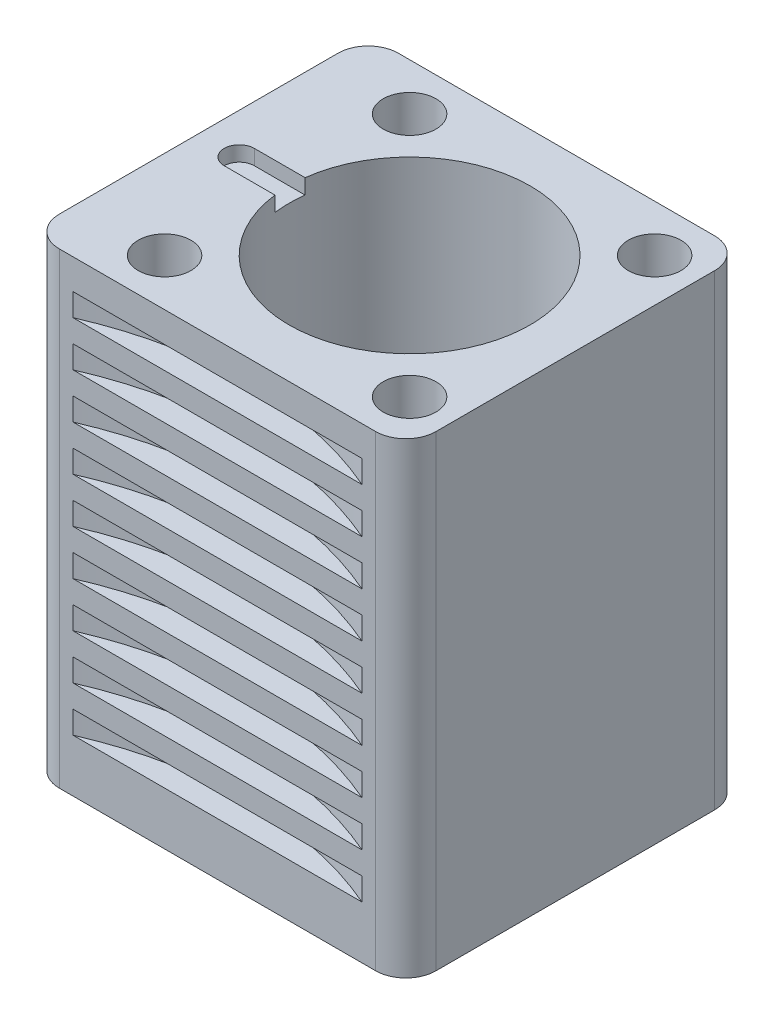
SolidWorks part; units mm, degrees
ref_plane "Front Plane" through (0, 0, 0) normal (0, 0, 1) x (1, 0, 0)
ref_plane "Top Plane" through (0, 0, 0) normal (0, 1, 0) x (1, 0, 0)
ref_plane "Right Plane" through (0, 0, 0) normal (1, 0, 0) x (0, 0, -1)
sketch "Sketch2" plane through (0, 0, 0) normal (0, 1, 0) x (1, 0, 0)
  line L1 (18, 22.5) -> (-24, 22.5)
  line L2 (22, 18.5) -> (22, -18.5)
  line L3 (18, -22.5) -> (-24, -22.5)
  line L4 (-28, 18.5) -> (-28, -18.5)
  arc A0 (-24, 22.5) -> (-28, 18.5) centre (-24, 18.5) ccw
  arc A1 (22, -18.5) -> (18, -22.5) centre (18, -18.5) cw
  arc A2 (-24, -22.5) -> (-28, -18.5) centre (-24, -18.5) cw
  arc A3 (18, 22.5) -> (22, 18.5) centre (18, 18.5) cw
  point P7 (-28, 22.5)
  point P10 (22, -22.5)
  point P15 (22, 22.5)
  dimension "D5" = 4
  dimension "D1" = 50
  dimension "D2" = 45
  dimension "D3" = 22
  dimension "D4" = 22.5
extrude "Boss-Extrude1" add sketch "Sketch2" along normal blind 62
sketch "Sketch3" plane through (0, 0, 0) normal (0, -1, 0) x (1, 0, 0)
  circle A0 centre (0, 0) radius 18
  dimension "D1" = 36
extrude "Boss-Extrude2" add sketch "Sketch3" along normal blind 2
sketch "Sketch4" plane through (0, -2, 0) normal (0, -1, 0) x (1, 0, 0)
  circle A0 centre (0, 0) radius 16
  dimension "D1" = 32
extrude "Cut-Extrude1" cut sketch "Sketch4" against normal through all
sketch "Sketch7" plane through (0, 62, 0) normal (0, 1, 0) x (1, 0, 0)
  line L0 (-28, 18.5) -> (-28, -18.5) construction
  line L1 (-22.61, 2) -> (-11.0093, 2)
  line L3 (-22.61, -2) -> (-11.0093, -2)
  line L4 (-11.0093, 2) -> (-11.0093, -2)
  arc A0 (-22.61, 2) -> (-22.61, -2) centre (-22.61, 0) ccw
  dimension "D1" = 4
  dimension "D2" = 2
  dimension "D3" = 5.39
extrude "Cut-Extrude2" cut sketch "Sketch7" against normal blind 2
sketch "Sketch8" plane through (0, 62, 0) normal (0, 1, 0) x (1, 0, 0)
  line L0 (0, 0) -> (23, 0) construction
  line L1 (0, 0) -> (16.2635, 16.2635) construction
  circle A0 centre (0, 0) radius 23 construction
  circle A1 centre (16.2635, 16.2635) radius 3.5
  circle A2 centre (16.2635, -16.2635) radius 3.5
  circle A3 centre (-16.2635, -16.2635) radius 3.5
  circle A4 centre (-16.2635, 16.2635) radius 3.5
  point P15 (0, 0)
  dimension "D1" = 46
  dimension "D3" = 7
  dimension "D2" = 45
  dimension "D4" = 4
extrude "Cut-Extrude3" cut sketch "Sketch8" against normal through all
ref_plane "Plane1" through (-3, 0, 0) normal (1, 0, 0) x (0, 0, -1)
sketch "Sketch9" plane through (-3, 0, 0) normal (1, 0, 0) x (0, 0, -1)
  line L0 (-22.5, 62) -> (-22.5, 0) construction
  line L1 (-18.5, 58) -> (-66.5, 58)
  line L2 (-18.5, 58) -> (-18.5, 55)
  line L3 (-18.5, 55) -> (-66.5, 55)
  line L4 (-66.5, 58) -> (-66.5, 55)
  line L5 (-18.5, 62) -> (-22.5, 62) construction
  point P4 (-18.5, 56.5)
  dimension "D1" = 4
  dimension "D2" = 4
  dimension "D3" = 48
  dimension "D4" = 3
revolve "Cut-Revolve1" cut sketch "Sketch9" angle 360 about L4
pattern_linear "LPattern1" count 9 spacing 6 along (0, -1, 0) of "Cut-Revolve1"
mirror "Mirror1" about plane through (0, 0, 0) normal (0, 0, 1) of "LPattern1", "Cut-Revolve1"
sketch "Sketch11" plane through (0, 0, 0) normal (0, 0, 1) x (1, 0, 0)
  line L0 (-24, 62) -> (-28, 62) construction
  line L1 (-24, 58) -> (-72, 58)
  line L2 (-24, 58) -> (-24, 55)
  line L3 (-24, 55) -> (-72, 55)
  line L4 (-72, 58) -> (-72, 55)
  line L5 (-28, 62) -> (-28, 0) construction
  dimension "D1" = 4
  dimension "D2" = 4
  dimension "D3" = 48
  dimension "D4" = 3
revolve "Cut-Revolve3" cut sketch "Sketch11" angle 360 about L4
pattern_linear "LPattern2" count 9 spacing 6 along (0, -1, 0) of "Cut-Revolve3"
